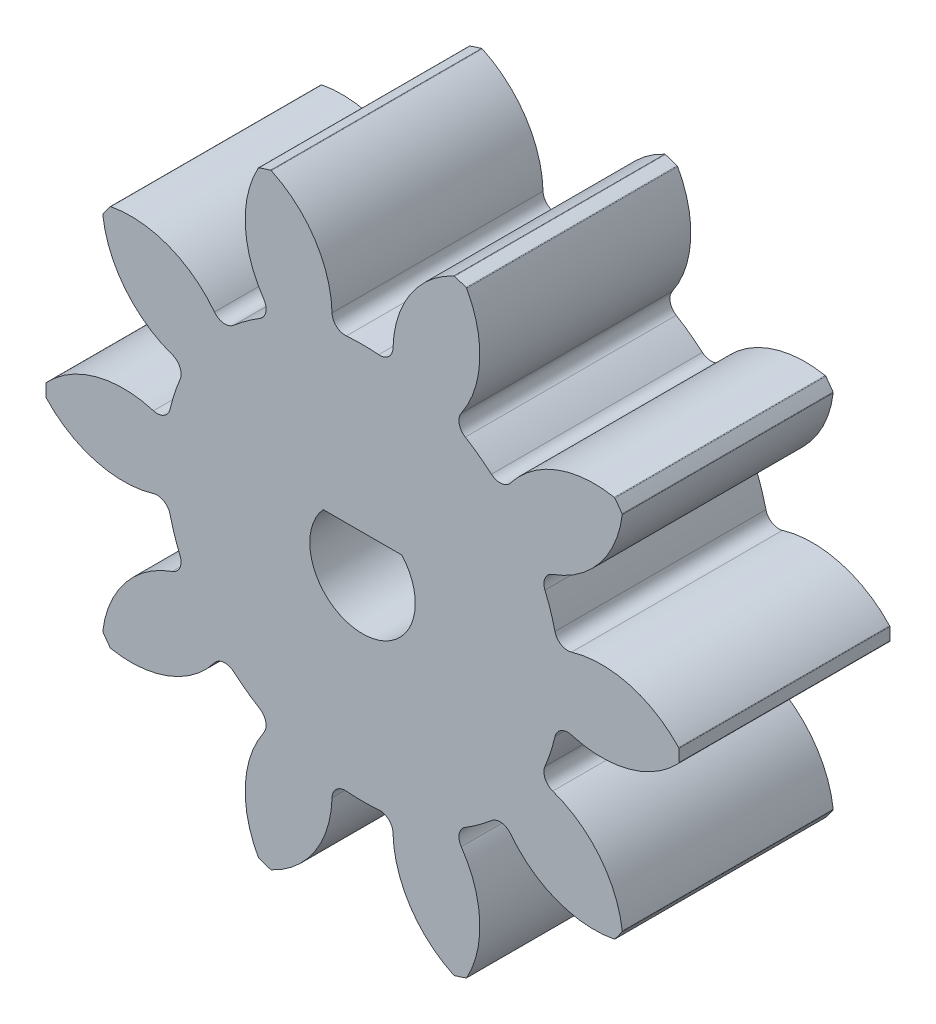
SolidWorks part; units mm, degrees
material "Barra Redonda SAE 1020 - 2\""
ref_plane "Plano frontal" through (0, 0, 0) normal (0, 0, 1) x (1, 0, 0)
ref_plane "Plano superior" through (0, 0, 0) normal (0, 1, 0) x (1, 0, 0)
ref_plane "Plano direito" through (0, 0, 0) normal (1, 0, 0) x (0, 0, -1)
sketch "Esboço1" plane through (0, 0, 0) normal (0, 1, 0) x (1, 0, 0)
  line L0 (0, 0) -> (0, -42.215) construction
  line L1 (0, 0) -> (18, 0)
  line L2 (0, 0) -> (0, 12)
  line L3 (0, 12) -> (18, 12)
  line L4 (18, 0) -> (18, 12)
  dimension "D1" = 12
  dimension "D2" = 36
revolve "Revolução1" add sketch "Esboço1" angle 360 about L0
sketch "Esboço2" plane through (0, 0, 0) normal (0, 0, 1) x (1, 0, 0)
  line L0 (0, 0) -> (0, 93.3393) construction
  line L1 (0, 0) -> (-2.5334, 14.7845) construction
  line L2 (0, 0) -> (-9.174, 28.2345) construction
  line L3 (-2.5334, 14.7845) -> (-4.587, 14.1173) construction
  arc A0 (1.7689, 11.109) -> (-1.7689, 11.109) centre (0, 0) ccw
  arc A1 (5.2426, 17.2462) -> (-5.2426, 17.2462) centre (0, 0) ccw
  circle A2 centre (0, 0) radius 15 construction
  circle A3 centre (0, 0) radius 14.0954 construction
  arc A4 (-1.7689, 11.109) -> (-5.2426, 17.2462) centre (-7.7306, 11.7863) ccw
  arc A5 (5.2426, 17.2462) -> (1.7689, 11.109) centre (7.7306, 11.7863) ccw
  dimension "D1" = 22.498
  dimension "D2" = 36.0508
  dimension "D3" = 30
  dimension "D6" = 28.1908
  dimension "D7" = 6
  dimension "D4" = 18
  dimension "D5" = 2.1593
extrude "Corte-extrusão1" cut sketch "Esboço2" against normal through all
fillet "Filete3" radius 0.06 2 edges at (-5.2078, 17.2302, -6) (5.2078, 17.2302, -6)
fillet "Filete4" radius 0.751 2 edges at (-1.7689, 11.109, -6) (1.7689, 11.109, -6)
pattern_circular "PadrãoCircular1" count 10 over 360 about axis through (0, 0, 0) along (0, 0, 1) of "Corte-extrusão1", "Filete3", "Filete4"
sketch "Esboço3" plane through (0, 0, -12) normal (0, 0, -1) x (-1, 0, 0)
  line L0 (-2.2361, 2) -> (2.2361, 2)
  arc A0 (-2.2361, 2) -> (2.2361, 2) centre (0, 0) ccw
  dimension "D1" = 6
  dimension "D2" = 2
extrude "Corte-extrusão2" cut sketch "Esboço3" against normal through all contours L0 A0
